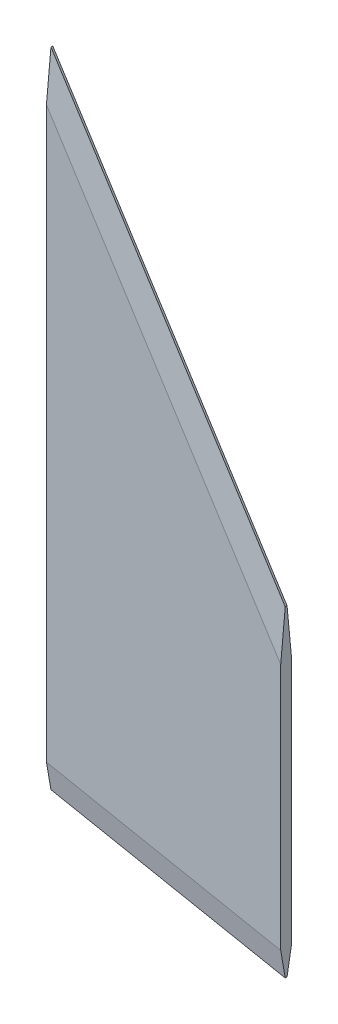
SolidWorks part; units mm, degrees
material "Hexcel AS4C (3000 Filaments)"
ref_plane "Front Plane" through (0, 0, 0) normal (0, 0, 1) x (1, 0, 0)
ref_plane "Top Plane" through (0, 0, 0) normal (0, 1, 0) x (1, 0, 0)
ref_plane "Right Plane" through (0, 0, 0) normal (1, 0, 0) x (0, 0, -1)
sketch "Sketch1" plane through (0, 0, 0) normal (0, 0, 1) x (1, 0, 0)
  line L0 (-60.9816, 99.3315) -> (-60.9816, -78.4685)
  line L1 (-60.9816, -78.4685) -> (3.7884, -91.1685)
  line L2 (3.7884, -91.1685) -> (3.7884, -2.2685)
  line L3 (3.7884, -2.2685) -> (-60.9816, 99.3315)
extrude "Boss-Extrude1" add sketch "Sketch1" along normal mid plane 3
chamfer "Chamfer1" distance 1.25 angle 80 4 edges at (-28.5966, -84.8185, -1.5) (-28.5966, -84.8185, 1.5) (-28.5966, 48.5315, -1.5) (-28.5966, 48.5315, 1.5)
